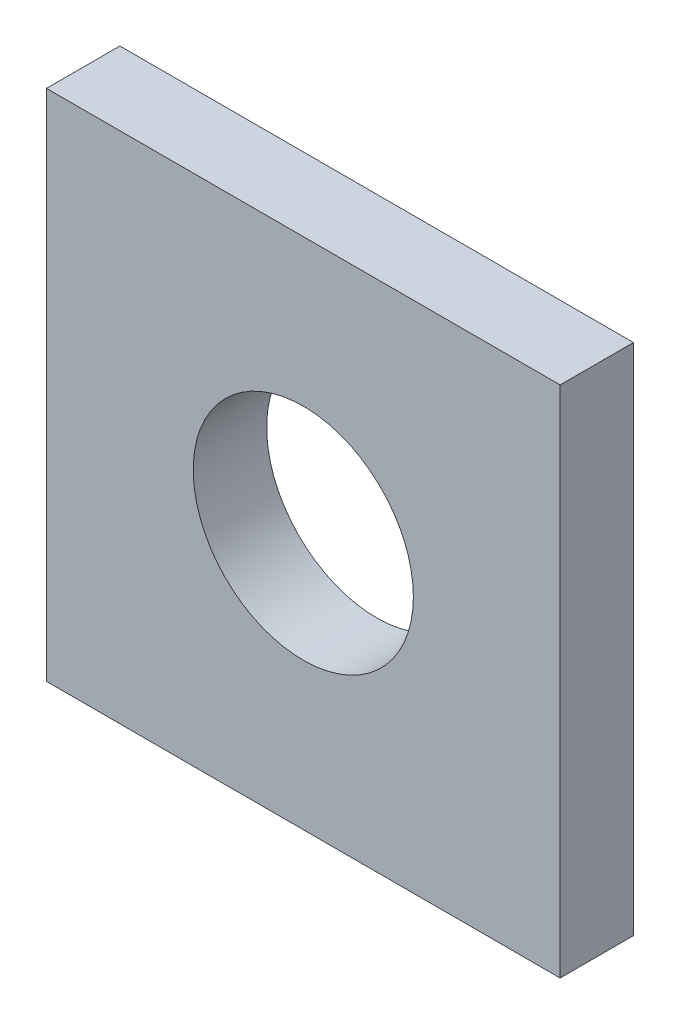
SolidWorks part; units mm, degrees
ref_plane "前视基准面" through (0, 0, 0) normal (0, 0, 1) x (1, 0, 0)
ref_plane "上视基准面" through (0, 0, 0) normal (0, 1, 0) x (1, 0, 0)
ref_plane "右视基准面" through (0, 0, 0) normal (1, 0, 0) x (0, 0, -1)
sketch "草图1" plane through (0, 0, 0) normal (0, 0, 1) x (1, 0, 0)
  line L1 (-35, -35) -> (35, -35)
  line L2 (-35, -35) -> (-35, 35)
  line L3 (-35, 35) -> (35, 35)
  line L4 (35, -35) -> (35, 35)
  line L5 (-35, -35) -> (35, 35) construction
  line L6 (-35, 35) -> (35, -35) construction
  circle A0 centre (0, 0) radius 15
  point P0 (0, 0)
  dimension "D3" = 30
  dimension "D1" = 70
  dimension "D2" = 70
extrude "凸台-拉伸1" add sketch "草图1" along normal blind 10
scale "缩放比例1" bodies to scale 106 scale about origin uniform scaling yes scale factor 0.6
